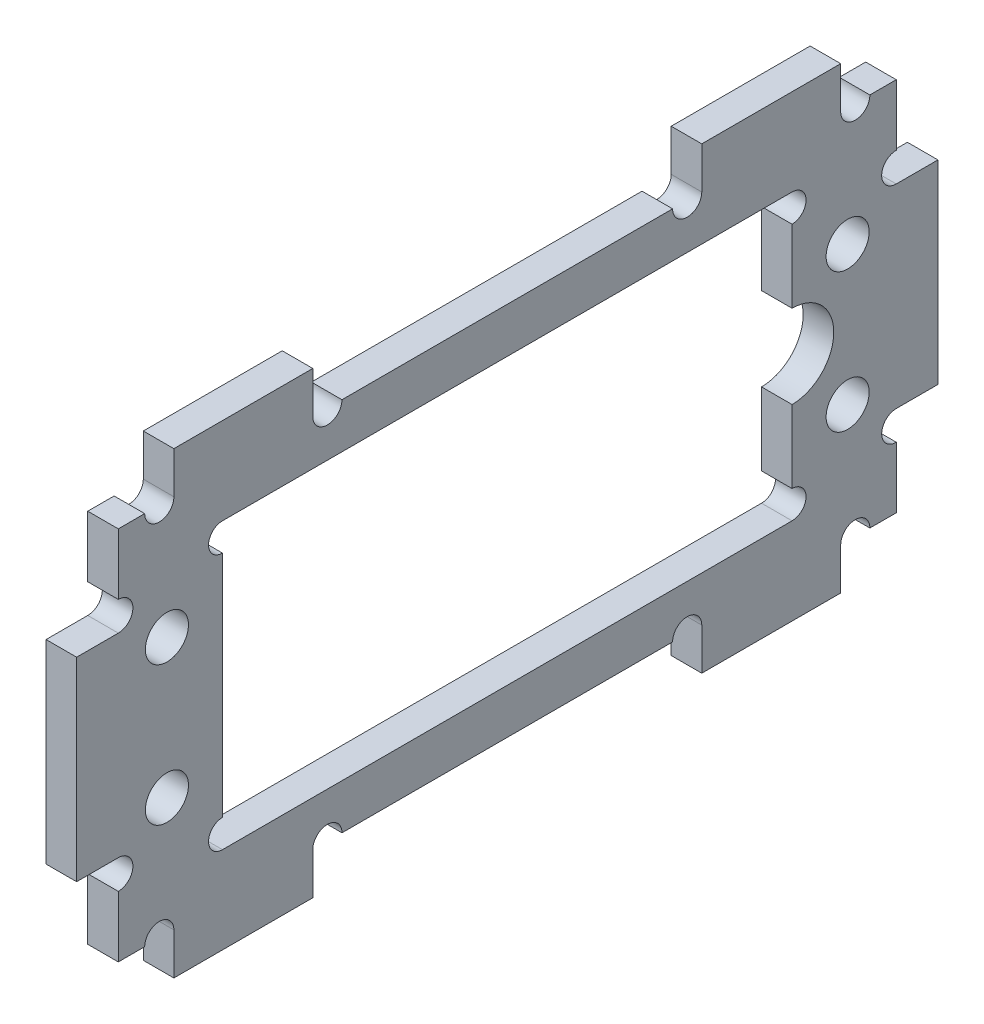
SolidWorks part; units mm, degrees
material "Thornel Mat VMA"
ref_plane "前视基准面" through (0, 0, 0) normal (0, 0, 1) x (1, 0, 0)
ref_plane "上视基准面" through (0, 0, 0) normal (0, 1, 0) x (1, 0, 0)
ref_plane "右视基准面" through (0, 0, 0) normal (1, 0, 0) x (0, 0, -1)
sketch "草图1" plane through (0, 0, 0) normal (1, 0, 0) x (0, 0, -1)
  line L0 (-24, 13.5) -> (-24, 16.5)
  line L1 (24.5, -5) -> (-24.5, -5) construction
  line L2 (24.5, -5) -> (24.5, 5) construction
  line L3 (24.5, 5) -> (-24.5, 5) construction
  line L4 (-24.5, -5) -> (-24.5, 5) construction
  line L5 (24.5, -5) -> (-24.5, 5) construction
  line L6 (24.5, 5) -> (-24.5, -5) construction
  line L7 (28, -13.5) -> (24, -13.5)
  line L8 (28, -13.5) -> (28, -7)
  line L9 (28, 13.5) -> (24, 13.5)
  line L10 (-28, -13.5) -> (-28, -7)
  line L11 (28, -13.5) -> (-28, 13.5) construction
  line L12 (28, 13.5) -> (-28, -13.5) construction
  line L13 (-24, 16.5) -> (-14, 16.5)
  line L14 (-14, 16.5) -> (-14, 13.5)
  line L15 (-19, 16.5) -> (-19, 8.4151) construction
  line L16 (-24, 13.5) -> (-28, 13.5)
  line L17 (0, 0) -> (0, 8.4151) construction
  line L18 (14, 16.5) -> (14, 13.5)
  line L19 (24, 16.5) -> (14, 16.5)
  line L20 (24, 13.5) -> (24, 16.5)
  line L21 (14, 13.5) -> (-14, 13.5)
  line L22 (0, 0) -> (14.1918, 0) construction
  line L23 (24, -13.5) -> (24, -16.5)
  line L24 (24, -16.5) -> (14, -16.5)
  line L25 (14, -16.5) -> (14, -13.5)
  line L26 (-14, -16.5) -> (-14, -13.5)
  line L27 (-24, -16.5) -> (-14, -16.5)
  line L28 (-24, -13.5) -> (-24, -16.5)
  line L29 (-24, -13.5) -> (-28, -13.5)
  line L30 (14, -13.5) -> (-14, -13.5)
  line L31 (20.5, 3) -> (20.5, 10.25)
  line L32 (20.5, -10.25) -> (-20.5, -10.25)
  line L33 (20.5, -10.25) -> (20.5, -3)
  line L34 (20.5, 10.25) -> (-20.5, 10.25)
  line L35 (-20.5, -10.25) -> (-20.5, 10.25)
  line L36 (20.5, -10.25) -> (-20.5, 10.25) construction
  line L37 (20.5, 10.25) -> (-20.5, -10.25) construction
  line L38 (-28, 7) -> (-31, 7)
  line L39 (-31, 7) -> (-31, -7)
  line L40 (-31, -7) -> (-28, -7)
  line L41 (-28, 7) -> (-28, 13.5)
  line L42 (31, -7) -> (28, -7)
  line L43 (28, 7) -> (31, 7)
  line L44 (31, 7) -> (31, -7)
  line L45 (28, 7) -> (28, 13.5)
  circle A0 centre (-24.5, 5) radius 1.55
  circle A1 centre (24.5, 5) radius 1.55
  circle A2 centre (24.5, -5) radius 1.55
  circle A3 centre (-24.5, -5) radius 1.55
  circle A4 centre (-25.05, 13.5) radius 1.05
  circle A5 centre (-12.95, 13.5) radius 1.05
  circle A6 centre (25.05, 13.5) radius 1.05
  circle A7 centre (12.95, 13.5) radius 1.05
  circle A8 centre (25.05, -13.5) radius 1.05
  circle A9 centre (12.95, -13.5) radius 1.05
  circle A10 centre (-12.95, -13.5) radius 1.05
  circle A11 centre (-25.05, -13.5) radius 1.05
  arc A12 (20.5, -3) -> (20.5, 3) centre (20.5, 0) ccw
  circle A13 centre (-28, 8.05) radius 1.05
  circle A14 centre (-28, -8.05) radius 1.05
  circle A15 centre (28, -8.05) radius 1.05
  circle A16 centre (28, 8.05) radius 1.05
  circle A17 centre (-20.5, 9.245) radius 1.005
  circle A18 centre (20.5, 9.245) radius 1.005
  circle A19 centre (20.5, -9.245) radius 1.005
  circle A20 centre (-20.5, -9.245) radius 1.005
  point P0 (0, 0)
  point P10 (0, 0)
  dimension "D1" = 3.1
  dimension "D8" = 2.1
  dimension "D12" = 6
  dimension "D15" = 2.01
  dimension "D2" = 49
  dimension "D3" = 10
  dimension "D4" = 27
  dimension "D5" = 3.5
  dimension "D6" = 10
  dimension "D7" = 9
  dimension "D9" = 3
  dimension "D10" = 20.5
  dimension "D11" = 41
  dimension "D13" = 14
  dimension "D14" = 3
extrude "凸台-拉伸1" add sketch "草图1" along normal blind 2.2 contours L29 A11 L28 L27 L26 A10 L30 A9 L25 L24 L23 A8 L7 L8 L9 A6 L20 L19 L18 A7 L21 A5 L14 L13 L0 A4 L16 L10 A12 L33 L32 L35 L34 L31 A3 A2 A1 A0
